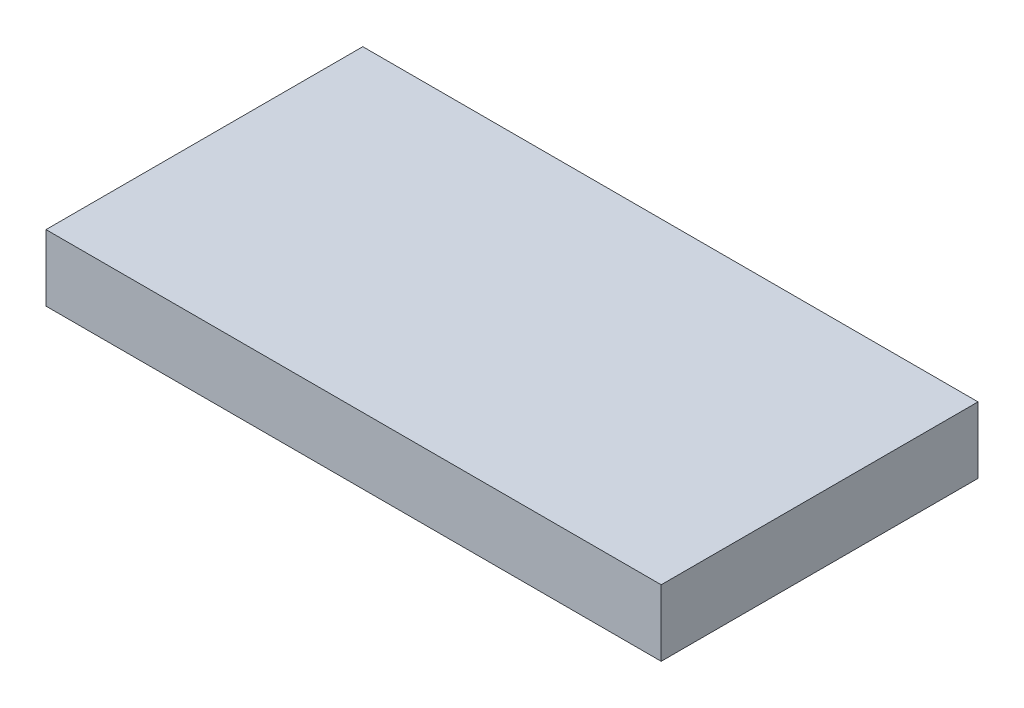
SolidWorks part; units mm, degrees
ref_plane "Front Plane" through (0, 0, 0) normal (0, 0, 1) x (1, 0, 0)
ref_plane "Top Plane" through (0, 0, 0) normal (0, 1, 0) x (1, 0, 0)
ref_plane "Right Plane" through (0, 0, 0) normal (1, 0, 0) x (0, 0, -1)
sketch "Sketch1" plane through (0, 0, 0) normal (0, 1, 0) x (1, 0, 0)
  line L1 (0, 0) -> (167, 0)
  line L2 (0, 0) -> (0, 86)
  line L3 (0, 86) -> (167, 86)
  line L4 (167, 0) -> (167, 86)
  dimension "D1" = 167
  dimension "D2" = 86
extrude "Boss-Extrude1" add sketch "Sketch1" along normal blind 18
